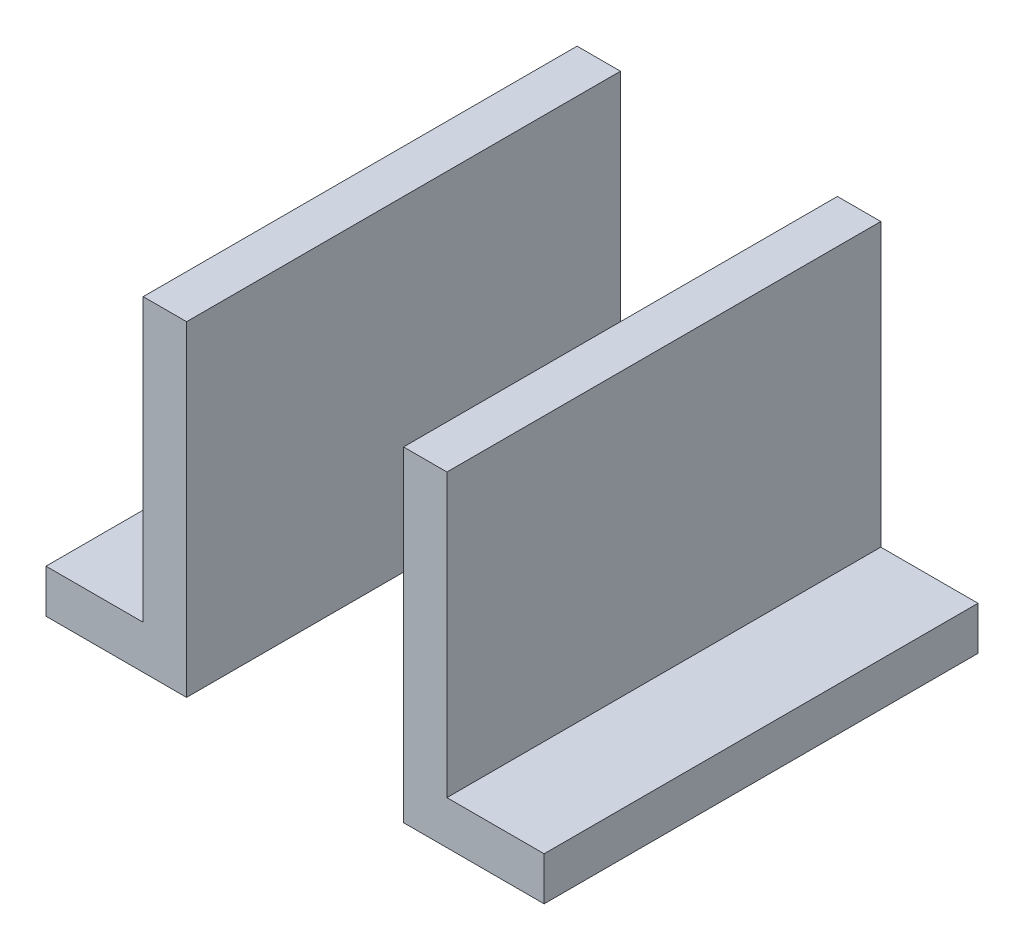
SolidWorks part; units mm, degrees
ref_plane "Front Plane" through (0, 0, 0) normal (0, 0, 1) x (1, 0, 0)
ref_plane "Top Plane" through (0, 0, 0) normal (0, 1, 0) x (1, 0, 0)
ref_plane "Right Plane" through (0, 0, 0) normal (1, 0, 0) x (0, 0, -1)
sketch "Sketch1" plane through (0, 0, 0) normal (0, 0, 1) x (1, 0, 0)
  line L0 (0, 0) -> (0, 22.5728) construction
  line L1 (-57.404, -45.4855) -> (-25, -45.4855)
  line L2 (25, 29.5145) -> (35, 29.5145)
  line L3 (35, 29.5145) -> (35, -35.4855)
  line L4 (35, -35.4855) -> (57.404, -35.4855)
  line L5 (57.404, -35.4855) -> (57.404, -45.4855)
  line L6 (57.404, -45.4855) -> (25, -45.4855)
  line L7 (-57.404, -35.4855) -> (-57.404, -45.4855)
  line L8 (25, 29.5145) -> (25, -45.4855)
  line L9 (-35, -35.4855) -> (-57.404, -35.4855)
  line L10 (-35, 29.5145) -> (-35, -35.4855)
  line L11 (-25, 29.5145) -> (-35, 29.5145)
  line L12 (-25, 29.5145) -> (-25, -45.4855)
  dimension "D1" = 10
  dimension "D2" = 75
  dimension "D3" = 10
  dimension "D4" = 25
extrude "Boss-Extrude1" add sketch "Sketch1" along normal blind 100
